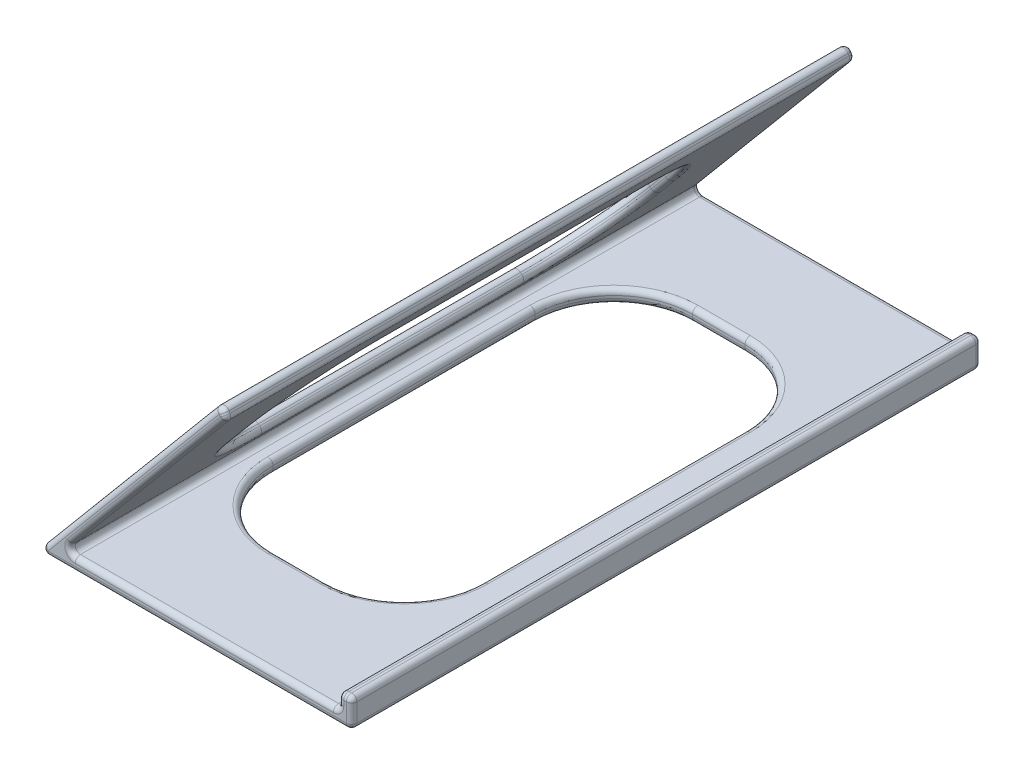
SolidWorks part; units mm, degrees
ref_plane "Front" through (0, 0, 0) normal (0, 0, 1) x (1, 0, 0)
ref_plane "Top" through (0, 0, 0) normal (0, 1, 0) x (1, 0, 0)
ref_plane "Right" through (0, 0, 0) normal (1, 0, 0) x (0, 0, -1)
sketch "Sketch2" plane through (0, 0, 0) normal (0, 0, 1) x (1, 0, 0)
  line L0 (0, 0) -> (-76.2, 0)
  line L1 (-76.2, 0) -> (-31.8543, 52.8491)
  line L2 (-31.8543, 52.8491) -> (-30.2668, 50.0995)
  line L3 (-30.2668, 50.0995) -> (-69.6411, 3.175)
  line L4 (-69.6411, 3.175) -> (-3.175, 3.175)
  line L5 (0, 3.175) -> (0, 0)
  line L6 (0, 3.175) -> (0, 6.985)
  line L7 (0, 6.985) -> (-3.175, 6.985)
  line L8 (-3.175, 6.985) -> (-3.175, 3.175)
  dimension "D1" = 76.2
  dimension "D2" = 50
  dimension "D3" = 3.175
  dimension "D4" = 3.175
  dimension "D5" = 3.175
  dimension "D6" = 3.81
  dimension "D7" = 60
extrude "Boss-Extrude2" add sketch "Sketch2" along normal blind 152.4
sketch "Sketch3" plane through (0, 0, 0) normal (0, -1, 0) x (-1, 0, 0)
  line L1 (12.7, -127) -> (63.5, -127)
  line L2 (12.7, -127) -> (12.7, -25.4)
  line L3 (12.7, -25.4) -> (63.5, -25.4)
  line L4 (63.5, -127) -> (63.5, -25.4)
  line L5 (76.2, -152.4) -> (0, -152.4) construction
  line L6 (76.2, 0) -> (0, 0) construction
  line L7 (76.2, -152.4) -> (76.2, 0) construction
  line L8 (0, -152.4) -> (0, 0) construction
  dimension "D1" = 25.4
  dimension "D2" = 25.4
  dimension "D3" = 12.7
  dimension "D4" = 12.7
extrude "Cut-Extrude2" cut sketch "Sketch3" against normal up to surface (3.175 mm away) and the other way through all up to face at (-36.4081, 3.175, 76.2)
sketch "Sketch4" plane through (-44.716, 37.5212, 0) normal (-0.766, 0.6428, 0) x (0, 0, 1)
  line L0 (152.4, -48.9804) -> (0, -48.9804) construction
  line L1 (127, -36.2804) -> (25.4, -36.2804)
  line L2 (127, -36.2804) -> (127, 7.3092)
  line L3 (127, 7.3092) -> (25.4, 7.3092)
  line L4 (25.4, -36.2804) -> (25.4, 7.3092)
  line L5 (0, 20.0092) -> (0, -48.9804) construction
  line L6 (152.4, 20.0092) -> (0, 20.0092) construction
  line L7 (152.4, 20.0092) -> (152.4, -48.9804) construction
  dimension "D1" = 12.7
  dimension "D2" = 25.4
  dimension "D3" = 12.7
  dimension "D4" = 25.4
extrude "Cut-Extrude3" cut sketch "Sketch4" against normal up to surface (2.9835 mm away) contours L2 L1 L4 L3 up to face at (-49.954, 26.6372, 76.2)
fillet "Fillet1" radius 19.05 4 edges at (-66.8938, 8.7699, 25.4) (-66.8938, 8.7699, 127) (-38.875, 42.1614, 127) (-38.875, 42.1614, 25.4)
fillet "Fillet2" radius 19.05 4 edges at (-12.7, 1.5875, 127) (-12.7, 1.5875, 25.4) (-63.5, 1.5875, 127) (-63.5, 1.5875, 25.4)
fillet "Fillet3" radius 1.27 56 edges at (-40.0178, 43.1203, 76.2) (-54.0272, 26.4245, 25.4) (-68.0366, 9.7288, 76.2) (-54.0272, 26.4245, 127) (-51.7417, 24.5068, 25.4) (-65.7511, 7.811, 76.2) (-51.7417, 24.5068, 127) (-37.7322, 41.2026, 76.2) (-63.5, 3.175, 76.2) (-38.1, 3.175, 25.4) (-12.7, 3.175, 76.2) (-38.1, 3.175, 127) (0, 3.4925, 0) (-1.5875, 6.985, 0) (-3.175, 5.08, 0) (-36.4081, 3.175, 0) (-49.954, 26.6372, 0) (-31.0606, 51.4743, 0) (-54.0272, 26.4245, 0) (-38.1, 0, 0) (0, 3.4925, 152.4) (-1.5875, 6.985, 152.4) (-3.175, 5.08, 152.4) (-36.4081, 3.175, 152.4) (-49.954, 26.6372, 152.4) (-31.0606, 51.4743, 152.4) (-54.0272, 26.4245, 152.4) (-38.1, 0, 152.4) (0, 0, 76.2) (-76.2, 0, 76.2) (-31.8543, 52.8491, 76.2) (-30.2668, 50.0995, 76.2) (-69.6411, 3.175, 76.2) (-3.175, 3.175, 76.2) (-3.175, 6.985, 76.2) (0, 6.985, 76.2) (-38.1, 0, 127) (-63.5, 0, 76.2) (-38.1, 0, 25.4) (-12.7, 0, 76.2) (-64.4501, 14.003, 30.9796) (-62.1646, 12.0852, 30.9796) (-64.4501, 14.003, 121.4204) (-62.1646, 12.0852, 121.4204) (-43.6043, 38.8461, 121.4204) (-41.3187, 36.9283, 121.4204) (-43.6043, 38.8461, 30.9796) (-41.3187, 36.9283, 30.9796) (-18.2796, 0, 121.4204) (-18.2796, 3.175, 121.4204) (-18.2796, 0, 30.9796) (-18.2796, 3.175, 30.9796) (-57.9204, 0, 121.4204) (-57.9204, 3.175, 121.4204) (-57.9204, 0, 30.9796) (-57.9204, 3.175, 30.9796)
